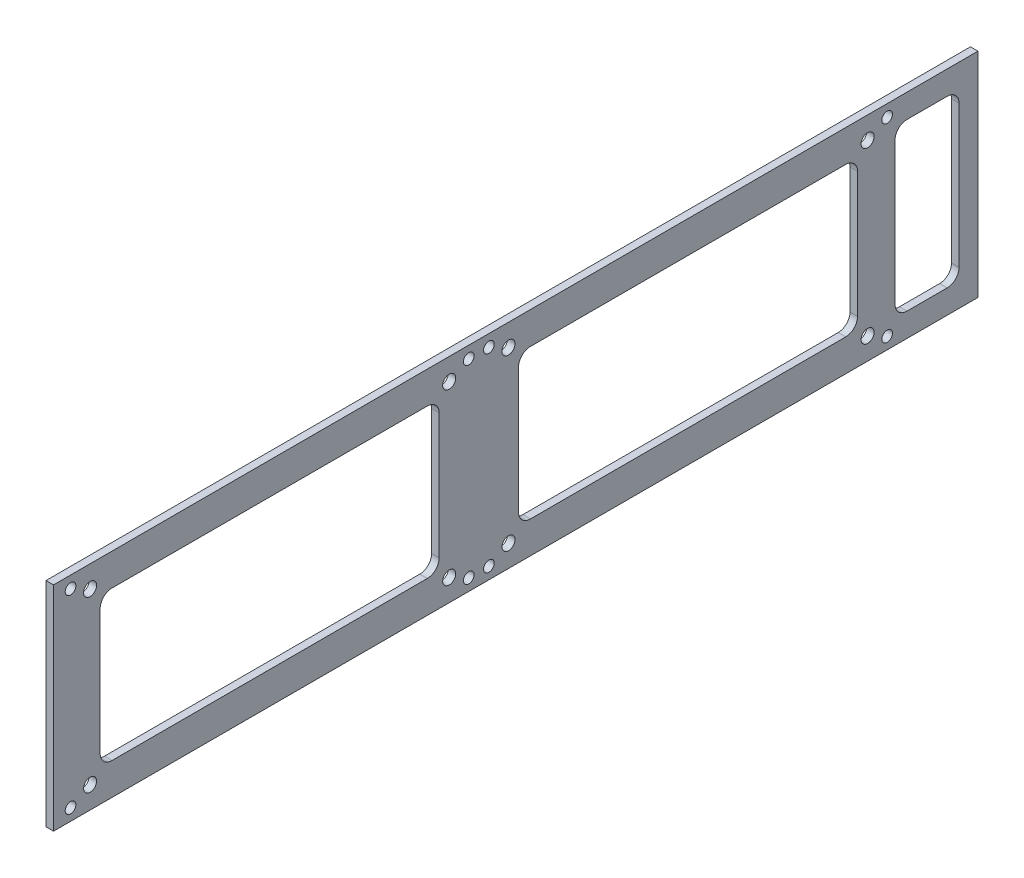
SolidWorks part; units mm, degrees
ref_plane "Front Plane" through (0, 0, 0) normal (0, 0, 1) x (1, 0, 0)
ref_plane "Top Plane" through (0, 0, 0) normal (0, 1, 0) x (1, 0, 0)
ref_plane "Right Plane" through (0, 0, 0) normal (1, 0, 0) x (0, 0, -1)
sketch "Sketch1" plane through (0, 0, 0) normal (1, 0, 0) x (0, 0, -1)
  line L1 (-195, -45) -> (195, -45)
  line L2 (-195, -45) -> (-195, 45)
  line L3 (-195, 45) -> (195, 45)
  line L4 (195, -45) -> (195, 45)
  line L5 (-195, -45) -> (195, 45) construction
  line L6 (-195, 45) -> (195, -45) construction
  point P0 (0, 0)
  dimension "D1" = 90
  dimension "D2" = 390
extrude "Boss-Extrude1" add sketch "Sketch1" along normal blind 3.175
sketch "Sketch2" plane through (3.175, 0, 0) normal (1, 0, 0) x (0, 0, -1)
  line L0 (1.175, -31.5) -> (144.175, -31.5)
  line L1 (-175.325, -31.5) -> (-32.325, -31.5)
  line L2 (-175.325, -31.5) -> (-175.325, 31.5)
  line L3 (-175.325, 31.5) -> (-32.325, 31.5)
  line L4 (-32.325, -31.5) -> (-32.325, 31.5)
  line L5 (-175.325, -31.5) -> (-32.325, 31.5) construction
  line L6 (-175.325, 31.5) -> (-32.325, -31.5) construction
  line L7 (-195, 45) -> (-195, -45) construction
  line L8 (1.175, -31.5) -> (1.175, 31.5)
  line L9 (1.175, 31.5) -> (144.175, 31.5)
  line L10 (144.175, -31.5) -> (144.175, 31.5)
  line L11 (1.175, -31.5) -> (144.175, 31.5) construction
  line L12 (1.175, 31.5) -> (144.175, -31.5) construction
  point P0 (-103.825, 0)
  point P5 (72.675, 0)
  dimension "D1" = 63
  dimension "D2" = 143
  dimension "D3" = 91.175
  dimension "D4" = 2
extrude "Cut-Extrude1" cut sketch "Sketch2" against normal blind 3.175
hole_wizard "M5 Clearance Hole1" positions "Sketch3" profile "Sketch5" hole size "M5" standard "ANSI Metric" end condition through all
sketch "Sketch3" plane through (3.175, 0, 0) normal (1, 0, 0) x (0, 0, -1)
  line L1 (-179.575, -35.75) -> (-28.075, -35.75)
  line L2 (-179.575, -35.75) -> (-179.575, 35.75)
  line L3 (-179.575, 35.75) -> (-28.075, 35.75)
  line L4 (-28.075, -35.75) -> (-28.075, 35.75)
  line L5 (-179.575, -35.75) -> (-28.075, 35.75) construction
  line L6 (-179.575, 35.75) -> (-28.075, -35.75) construction
  line L8 (-3.075, -35.75) -> (148.425, -35.75)
  line L9 (-3.075, -35.75) -> (-3.075, 35.75)
  line L10 (-3.075, 35.75) -> (148.425, 35.75)
  line L11 (148.425, -35.75) -> (148.425, 35.75)
  line L12 (-3.075, -35.75) -> (148.425, 35.75) construction
  line L13 (-3.075, 35.75) -> (148.425, -35.75) construction
  line L14 (-195, 45) -> (-195, -45) construction
  point P1 (-103.825, 0)
  point P2 (-28.075, 35.75)
  point P101 (-179.575, -35.75)
  point P102 (-179.575, 35.75)
  point P103 (-28.075, -35.75)
  point P104 (72.675, 0)
  point P105 (148.425, 35.75)
  point P166 (-3.075, -35.75)
  point P167 (-3.075, 35.75)
  point P168 (148.425, -35.75)
  point P185 (0, 0)
  dimension "D1" = 91.175
  dimension "D2" = 176.5
  dimension "D3" = 71.5
  dimension "D4" = 151.5
  dimension "D5" = 151.5
sketch "Sketch5" plane through (3.175, 0, 103.825) normal (0, 1, 0) x (0, 0, -1)
  line L0 (0, 0) -> (0, 3.175)
  line L1 (0, 3.175) -> (2.75, 3.175)
  line L2 (2.75, 3.175) -> (2.75, 0)
  line L5 (2.75, 0) -> (0, 0)
  line L11 (0, -6.35) -> (0, 107.95) construction
  dimension "Thru Hole Dia." = 5.5
  dimension "Thru Hole Depth" = 3.175
sketch "Sketch6" plane through (3.175, 0, 0) normal (1, 0, 0) x (0, 0, -1)
  line L0 (195, -45) -> (195, 45) construction
  line L1 (160, -35) -> (187, -35)
  line L2 (160, -35) -> (160, 35)
  line L3 (160, 35) -> (187, 35)
  line L4 (187, -35) -> (187, 35)
  line L5 (160, -35) -> (187, 35) construction
  line L6 (160, 35) -> (187, -35) construction
  line L7 (195, 45) -> (-195, 45) construction
  point P0 (173.5, 0)
  dimension "D1" = 27
  dimension "D2" = 8
  dimension "D3" = 10
extrude "Cut-Extrude2" cut sketch "Sketch6" against normal blind 3.175
hole_wizard "M4 Clearance Hole2" positions "Sketch7" profile "Sketch8" hole size "M4" standard "ANSI Metric" end condition through all
sketch "Sketch7" plane through (3.175, 0, 0) normal (1, 0, 0) x (0, 0, -1)
  line L1 (-187.825, -40) -> (-19.825, -40)
  line L2 (-187.825, -40) -> (-187.825, 40)
  line L3 (-187.825, 40) -> (-19.825, 40)
  line L4 (-19.825, -40) -> (-19.825, 40)
  line L5 (-187.825, -40) -> (-19.825, 40) construction
  line L6 (-187.825, 40) -> (-19.825, -40) construction
  line L9 (-11.325, -40) -> (156.675, -40)
  line L10 (-11.325, -40) -> (-11.325, 40)
  line L11 (-11.325, 40) -> (156.675, 40)
  line L12 (156.675, -40) -> (156.675, 40)
  line L13 (-11.325, -40) -> (156.675, 40) construction
  line L14 (-11.325, 40) -> (156.675, -40) construction
  point P1 (-103.825, 0)
  point P2 (-19.825, 40)
  point P105 (-187.825, -40)
  point P106 (-187.825, 40)
  point P107 (-19.825, -40)
  point P175 (72.675, 0)
  point P176 (156.675, 40)
  point P243 (-11.325, -40)
  point P244 (-11.325, 40)
  point P245 (156.675, -40)
  dimension "D1" = 80
  dimension "D2" = 168
  dimension "D3" = 168
sketch "Sketch8" plane through (3.175, 0, 103.825) normal (0, 1, 0) x (0, 0, -1)
  line L0 (0, 0) -> (0, 3.175)
  line L1 (0, 3.175) -> (2.25, 3.175)
  line L2 (2.25, 3.175) -> (2.25, 0)
  line L5 (2.25, 0) -> (0, 0)
  line L11 (0, -6.35) -> (0, 107.95) construction
  dimension "Thru Hole Dia." = 4.5
  dimension "Thru Hole Depth" = 3.175
fillet "Fillet1" radius 5 12 edges at (1.5875, -31.5, 32.325) (1.5875, 31.5, 32.325) (1.5875, 31.5, 175.325) (1.5875, -31.5, 175.325) (1.5875, -31.5, -1.175) (1.5875, 31.5, -1.175) (1.5875, 31.5, -144.175) (1.5875, -31.5, -144.175) (1.5875, -35, -187) (1.5875, -35, -160) (1.5875, 35, -160) (1.5875, 35, -187)
